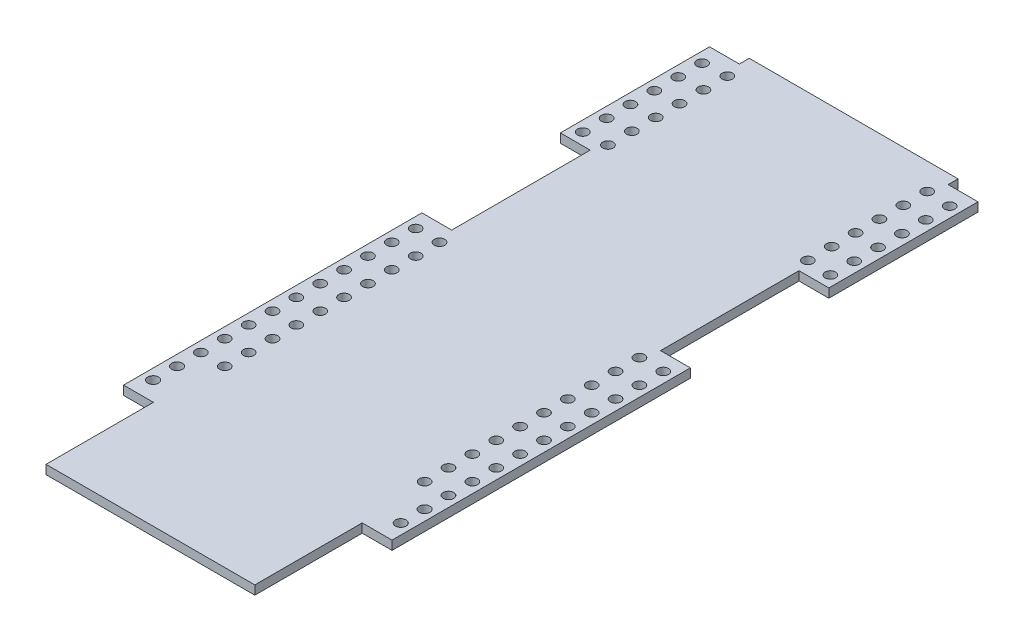
SolidWorks part; units mm, degrees
ref_plane "Front Plane" through (0, 0, 0) normal (0, 0, 1) x (1, 0, 0)
ref_plane "Top Plane" through (0, 0, 0) normal (0, 1, 0) x (1, 0, 0)
ref_plane "Right Plane" through (0, 0, 0) normal (1, 0, 0) x (0, 0, -1)
sketch "Sketch5" plane through (0, 0, 0) normal (0, 1, 0) x (1, 0, 0)
  line L0 (70, 36) -> (80, 36)
  line L1 (0, 0) -> (70, 0)
  line L2 (0, 0) -> (0, 235.74)
  line L3 (0, 235.74) -> (70, 235.74)
  line L4 (70, 0) -> (70, 235.74)
  line L5 (80, 36) -> (80, 136)
  line L6 (80, 136) -> (70, 136)
  line L7 (35, 235.74) -> (35, 0) construction
  line L8 (-10, 136) -> (0, 136)
  line L9 (-10, 36) -> (-10, 136)
  line L10 (0, 36) -> (-10, 36)
  dimension "D1" = 235.74
  dimension "D2" = 70
  dimension "D3" = 36
  dimension "D4" = 100
  dimension "D5" = 10
extrude "Boss-Extrude5" add sketch "Sketch5" along normal blind 3 contours L10 L2 L8 L9 | L7 L3 L2 L1 | L3 L7 L1 L4 | L5 L6 L4 L0
sketch "Sketch6" plane through (0, 3, 0) normal (0, 1, 0) x (1, 0, 0)
  point P0 (76.5, 50.4206)
  point P3 (76.5, 42.4206)
  point P6 (0, 0)
hole_wizard "M3 Clearance Hole1" positions "Sketch6" profile "Sketch7" hole size "M3" standard "ANSI Metric" end condition through all
sketch "Sketch7" plane through (76.5, 3, -50.4206) normal (1, 0, 0) x (0, 0, 1)
  line L0 (0, 0) -> (0, 3)
  line L1 (0, 3) -> (1.8, 3)
  line L2 (1.8, 3) -> (1.8, 0)
  line L5 (1.8, 0) -> (0, 0)
  line L11 (0, -6.35) -> (0, 107.95) construction
  dimension "Thru Hole Dia." = 3.6
  dimension "Thru Hole Depth" = 3
ref_plane "Plane1" through (35, 0, 0) normal (-1, 0, 0) x (0, 0, 1)
sketch "Sketch8" plane through (0, 3, 0) normal (0, 1, 0) x (1, 0, 0)
  line L0 (80, 36) -> (80, 136) construction
  circle A0 centre (76.5, 58.4206) radius 1.75
  circle A1 centre (76.5, 66.4206) radius 1.75
  circle A2 centre (76.5, 74.4206) radius 1.75
  circle A3 centre (76.5, 82.4206) radius 1.75
  circle A4 centre (76.5, 50.4206) radius 1.8 construction
  circle A6 centre (68.5, 58.4206) radius 1.75
  circle A7 centre (68.5, 66.4206) radius 1.75
  circle A8 centre (68.5, 74.4206) radius 1.75
  circle A9 centre (68.5, 82.4206) radius 1.75
  circle A10 centre (68.5, 90.4206) radius 1.75
  circle A11 centre (76.5, 90.4206) radius 1.75
  circle A12 centre (76.5, 98.4206) radius 1.75
  circle A13 centre (68.5, 98.4206) radius 1.75
  circle A14 centre (68.5, 106.4206) radius 1.75
  circle A15 centre (76.5, 106.4206) radius 1.75
  circle A16 centre (68.5, 114.4206) radius 1.75
  circle A17 centre (76.5, 114.4206) radius 1.75
  circle A18 centre (68.5, 122.4206) radius 1.75
  circle A19 centre (76.5, 122.4206) radius 1.75
  circle A20 centre (76.5, 130.4206) radius 1.75
  circle A21 centre (68.5, 130.4206) radius 1.75
  dimension "D1" = 3.5
  dimension "D3" = 8
  dimension "D7" = 8
  dimension "D29" = 3.5
  dimension "D30" = 3.5
  dimension "D31" = 3.5
  dimension "D32" = 3.5
  dimension "D33" = 3.5
  dimension "D34" = 3.5
  dimension "D2" = 3.5
  dimension "D4" = 8
  dimension "D5" = 8
  dimension "D6" = 8
  dimension "D8" = 8
  dimension "D9" = 8
  dimension "D10" = 8
  dimension "D11" = 8
  dimension "D12" = 8
  dimension "D13" = 8
  dimension "D14" = 8
  dimension "D15" = 8
  dimension "D16" = 8
  dimension "D17" = 8
  dimension "D18" = 8
  dimension "D19" = 8
  dimension "D20" = 8
  dimension "D21" = 8
  dimension "D22" = 8
  dimension "D23" = 8
  dimension "D24" = 8
  dimension "D25" = 8
  dimension "D26" = 8
  dimension "D27" = 8
  dimension "D28" = 8
extrude "Cut-Extrude1" cut sketch "Sketch8" against normal through all
sketch "Sketch10" plane through (0, 0, 0) normal (0, -1, 0) x (1, 0, 0)
  line L0 (70, -182.4206) -> (80, -182.4206)
  line L1 (70, -136) -> (70, -235.74) construction
  line L2 (80, -182.4206) -> (80, -232.4206)
  line L3 (80, -232.4206) -> (70, -232.4206)
  line L4 (70, -232.4206) -> (70, -182.4206)
  circle A0 centre (76.5, -186.4206) radius 1.75
  circle A1 centre (76.5, -194.4206) radius 1.75
  circle A2 centre (76.5, -202.4206) radius 1.75
  circle A3 centre (76.5, -210.4206) radius 1.75
  circle A4 centre (76.5, -130.4206) radius 1.75 construction
  circle A6 centre (76.5, -218.4206) radius 1.75
  circle A7 centre (76.5, -226.4206) radius 1.75
  dimension "D8" = 3.5
  dimension "D10" = 8
  dimension "D11" = 3.5
  dimension "D1" = 10
  dimension "D2" = 50
  dimension "D3" = 8
  dimension "D4" = 8
  dimension "D5" = 8
  dimension "D6" = 56
  dimension "D7" = 4
  dimension "D9" = 8
extrude "Boss-Extrude6" add sketch "Sketch10" against normal blind 3
sketch "Sketch11" plane through (0, 3, 0) normal (0, 1, 0) x (1, 0, 0)
  line L0 (68.5, 226.8866) -> (68.5, 182.9409) construction
  circle A0 centre (68.5, 226.8866) radius 1.75
  circle A6 centre (76.5, 226.4206) radius 1.75 construction
  circle A7 centre (68.5, 218.8866) radius 1.75
  circle A8 centre (68.5, 210.8866) radius 1.75
  circle A9 centre (68.5, 202.8866) radius 1.75
  circle A10 centre (68.5, 194.8866) radius 1.75
  circle A11 centre (68.5, 186.8866) radius 1.75
  circle A12 centre (76.5, 186.4206) radius 1.75 construction
  dimension "D2" = 8
  dimension "D1" = 8
  dimension "D3" = 8
  dimension "D4" = 8
  dimension "D5" = 8
  dimension "D6" = 8
extrude "Cut-Extrude2" cut sketch "Sketch11" against normal through all
mirror "Mirror1" about plane through (35, 0, 0) normal (-1, 0, 0) of "Cut-Extrude2", "Boss-Extrude6", "M3 Clearance Hole1", "Cut-Extrude1"
equation "\"Spacing\"=8"
equation "\"D3@Sketch11\"=\"Spacing\""
equation "\"D1@Sketch11\"=\"Spacing\""
equation "\"D4@Sketch11\"=\"Spacing\""
equation "\"D5@Sketch11\"=\"Spacing\""
equation "\"D6@Sketch11\"=\"Spacing\""
equation "\"D2@Sketch11\"=\"Spacing\""
